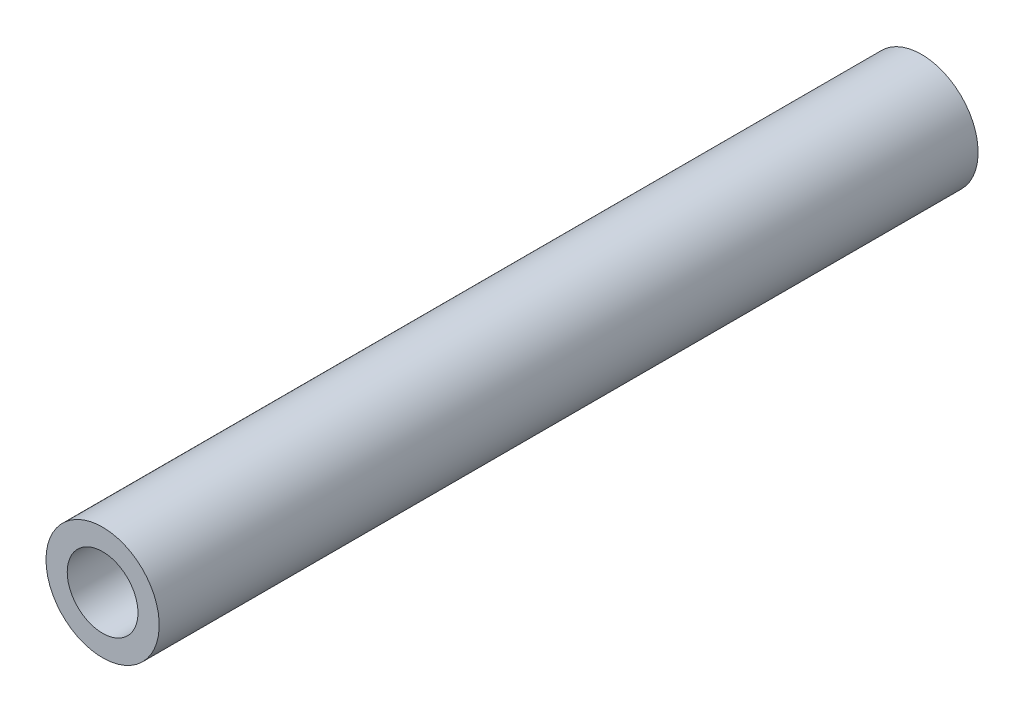
SolidWorks part; units mm, degrees
material "6061-T4 (SS)"
ref_plane "前视基准面" through (0, 0, 0) normal (0, 0, 1) x (1, 0, 0)
ref_plane "上视基准面" through (0, 0, 0) normal (0, 1, 0) x (1, 0, 0)
ref_plane "右视基准面" through (0, 0, 0) normal (1, 0, 0) x (0, 0, -1)
other "Configuration Table"
sketch "草图1" plane through (0, 0, 0) normal (0, 0, 1) x (1, 0, 0)
  circle A0 centre (0, 0) radius 4
  circle A1 centre (0, 0) radius 2.5
  dimension "D1" = 5
  dimension "D2" = 8
extrude "凸台-拉伸1" add sketch "草图1" along normal blind 57.87
